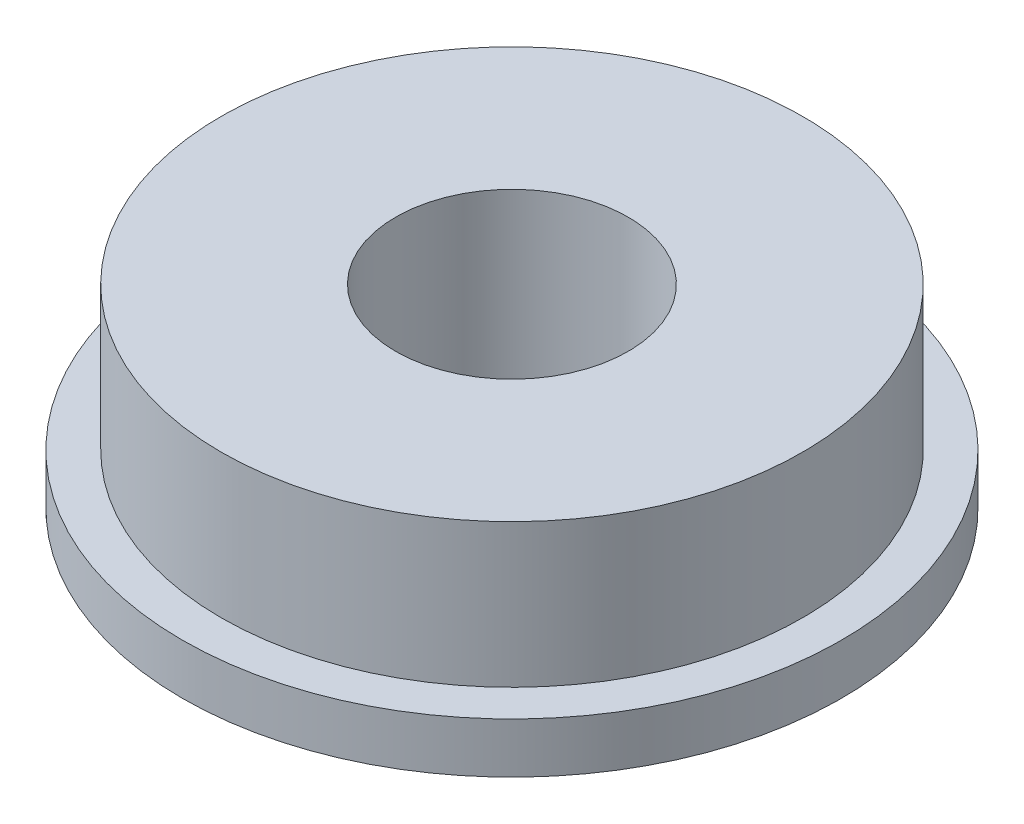
SolidWorks part; units mm, degrees
ref_plane "前视基准面" through (0, 0, 0) normal (0, 0, 1) x (1, 0, 0)
ref_plane "上视基准面" through (0, 0, 0) normal (0, 1, 0) x (1, 0, 0)
ref_plane "右视基准面" through (0, 0, 0) normal (1, 0, 0) x (0, 0, -1)
sketch "草图1" plane through (0, 0, 0) normal (0, 0, 1) x (1, 0, 0)
  line L0 (-3, 0) -> (-8.5, 0)
  line L1 (-8.5, 0) -> (-8.5, 1.3)
  line L2 (-8.5, 1.3) -> (-7.5, 1.3)
  line L3 (-7.5, 1.3) -> (-7.5, 5)
  line L4 (-7.5, 5) -> (-3, 5)
  line L5 (-3, 5) -> (-3, 0)
  line L6 (0, 9.4167) -> (0, -2.75) construction
  dimension "D1" = 6
  dimension "D2" = 17
  dimension "D3" = 15
  dimension "D4" = 5
  dimension "D5" = 1.3
revolve "旋转1" add sketch "草图1" angle 360 about L6
